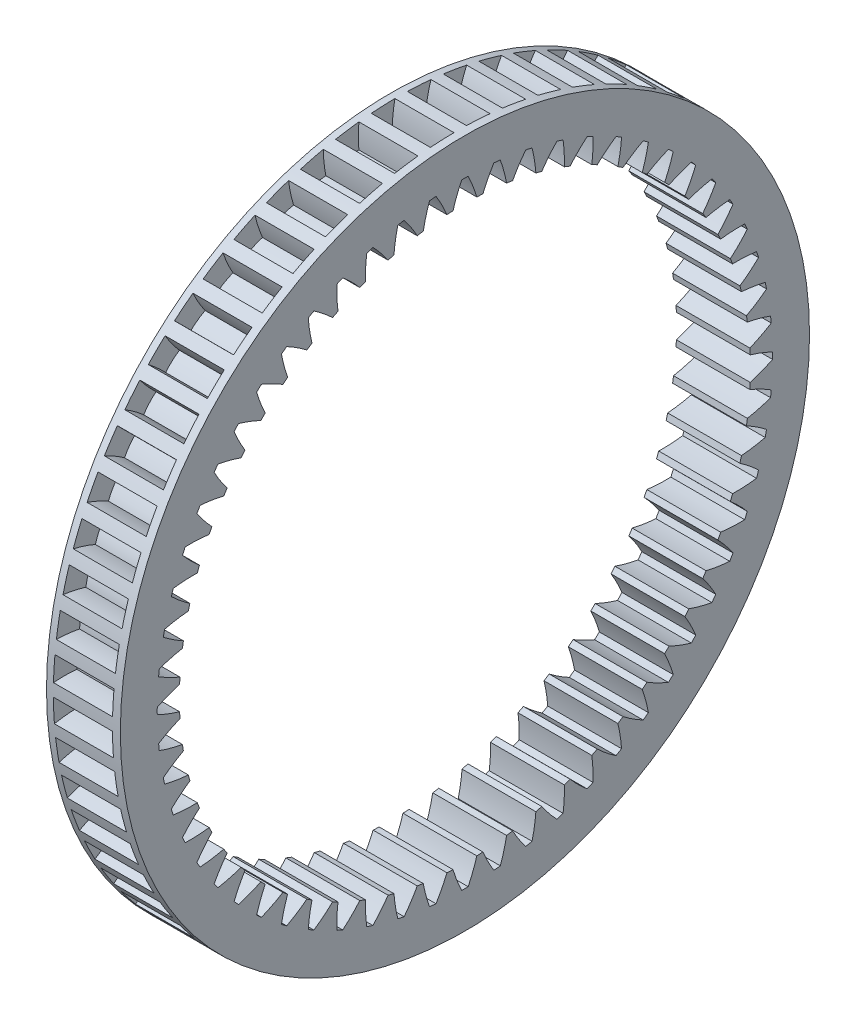
SolidWorks part; units mm, degrees
ref_plane "Front Plane" through (0, 0, 0) normal (0, 0, 1) x (1, 0, 0)
ref_plane "Top Plane" through (0, 0, 0) normal (0, 1, 0) x (1, 0, 0)
ref_plane "Right Plane" through (0, 0, 0) normal (1, 0, 0) x (0, 0, -1)
ref_plane "Plane1" through (0, 0, -17.7803) normal (0, 0, -1) x (-1, 0, 0)
sketch "Sketch1" plane through (0, 0, -17.7803) normal (0, 0, -1) x (-1, 0, 0)
  line L0 (3.4004, 104.6376) -> (3.4004, 34.6376)
  line L1 (3.4004, 34.6376) -> (5, 34.6376)
  line L2 (5, 34.6376) -> (5, 104.6376)
  line L3 (5, 104.6376) -> (3.4004, 104.6376)
  line L4 (3.4004, 34.6376) -> (5, 34.6376) construction
revolve "Revolve1" add sketch "Sketch1" angle 360 about L4
sketch "Sketch2" plane through (-5, 0, 0) normal (-1, 0, 0) x (0, 0, 1)
  arc A0 (-82.8676, 39.5668) -> (-82.8676, 35.7793) centre (-70.1186, 37.6731) ccw
  arc A1 (-87.571, 40.0464) -> (-82.8676, 39.5668) centre (-82.6586, 64.9218) ccw
  arc A2 (-87.571, 40.0464) -> (-87.3292, 42.5713) centre (-17.7803, 34.6376) cw
  arc A3 (-82.3917, 42.5765) -> (-87.3292, 42.5713) centre (-84.8336, 17.3751) ccw
  arc A4 (-81.9958, 46.3433) -> (-82.3917, 42.5765) centre (-69.5146, 43.1273) ccw
  arc A5 (-86.6233, 47.3118) -> (-81.9958, 46.3433) centre (-79.1376, 71.5375) ccw
  arc A6 (-86.6233, 47.3118) -> (-86.1189, 49.7977) centre (-17.7803, 34.6376) cw
  arc A7 (-81.2079, 49.2868) -> (-86.1189, 49.7977) centre (-86.2707, 24.4786) ccw
  arc A8 (-80.4204, 52.9915) -> (-81.2079, 49.2868) centre (-68.3437, 48.4885) ccw
  arc A9 (-84.9214, 54.4385) -> (-80.4204, 52.9915) centre (-74.9444, 77.749) ccw
  arc A10 (-84.9214, 54.4385) -> (-84.1599, 56.858) centre (-17.7803, 34.6376) cw
  arc A11 (-79.3291, 55.8365) -> (-84.1599, 56.858) centre (-86.9574, 31.6935) ccw
  arc A12 (-78.1587, 59.4386) -> (-79.3291, 55.8365) centre (-66.6189, 53.6979) ccw
  arc A13 (-82.4838, 61.3481) -> (-78.1587, 59.4386) centre (-70.1249, 83.4881) ccw
  arc A14 (-82.4838, 61.3481) -> (-81.4736, 63.6748) centre (-17.7803, 34.6376) cw
  arc A15 (-76.7761, 62.154) -> (-81.4736, 63.6748) centre (-86.8862, 38.9406) ccw
  arc A16 (-75.2356, 65.614) -> (-76.7761, 62.154) centre (-64.359, 58.6985) ccw
  arc A17 (-79.3373, 67.9652) -> (-75.2356, 65.614) centre (-64.7319, 88.692) ccw
  arc A18 (-79.3373, 67.9652) -> (-78.0895, 70.1735) centre (-17.7803, 34.6376) cw
  arc A19 (-73.5766, 68.17) -> (-78.0895, 70.1735) centre (-86.0579, 46.1405) ccw
  arc A20 (-71.6829, 71.45) -> (-73.5766, 68.17) centre (-61.5888, 63.4355) ccw
  arc A21 (-75.5164, 74.2171) -> (-71.6829, 71.45) centre (-58.8244, 93.3036) ccw
  arc A22 (-75.5164, 74.2171) -> (-74.0446, 76.2828) centre (-17.7803, 34.6376) cw
  arc A23 (-69.7659, 73.8186) -> (-74.0446, 76.2828) centre (-84.4814, 53.2145) ccw
  arc A24 (-67.5397, 76.8827) -> (-69.7659, 73.8186) centre (-58.3386, 67.857) ccw
  arc A25 (-71.063, 80.0353) -> (-67.5397, 76.8827) centre (-52.4673, 97.2725) ccw
  arc A26 (-71.063, 80.0353) -> (-69.3832, 81.9359) centre (-17.7803, 34.6376) cw
  arc A27 (-65.3856, 79.0379) -> (-69.3832, 81.9359) centre (-82.1742, 60.0849) ccw
  arc A28 (-62.8513, 81.8526) -> (-65.3856, 79.0379) centre (-54.6441, 71.9145) ccw
  arc A29 (-66.0257, 85.3562) -> (-62.8513, 81.8526) centre (-45.7302, 100.5552) ccw
  arc A30 (-66.0257, 85.3562) -> (-64.1565, 87.0708) centre (-17.7803, 34.6376) cw
  arc A31 (-60.4837, 83.7708) -> (-64.1565, 87.0708) centre (-79.1615, 66.6765) ccw
  arc A32 (-57.669, 86.3051) -> (-60.4837, 83.7708) centre (-50.5456, 75.5636) ccw
  arc A33 (-60.4599, 90.1214) -> (-57.669, 86.3051) centre (-38.6868, 103.1157) ccw
  arc A34 (-60.4599, 90.1214) -> (-58.4217, 91.6312) centre (-17.7803, 34.6376) cw
  arc A35 (-55.1139, 87.9654) -> (-58.4217, 91.6312) centre (-75.4763, 72.917) ccw
  arc A36 (-52.0498, 90.1916) -> (-55.1139, 87.9654) centre (-46.0882, 78.7643) ccw
  arc A37 (-54.4264, 94.2787) -> (-52.0498, 90.1916) centre (-31.4144, 104.9258) ccw
  arc A38 (-54.4264, 94.2787) -> (-52.2416, 95.5672) centre (-17.7803, 34.6376) cw
  arc A39 (-49.3351, 91.5757) -> (-52.2416, 95.5672) centre (-71.1589, 78.7382) ccw
  arc A40 (-46.0551, 93.4694) -> (-49.3351, 91.5757) centre (-41.3206, 81.4816) ccw
  arc A41 (-47.9915, 97.7825) -> (-46.0551, 93.4694) centre (-23.9925, 105.966) ccw
  arc A42 (-47.9915, 97.7825) -> (-45.684, 98.8356) centre (-17.7803, 34.6376) cw
  arc A43 (-43.2106, 94.5621) -> (-45.684, 98.8356) centre (-66.2567, 84.0762) ccw
  arc A44 (-39.7506, 96.1027) -> (-43.2106, 94.5621) centre (-36.2951, 83.6856) ccw
  arc A45 (-41.2256, 100.5945) -> (-39.7506, 96.1027) centre (-16.5027, 106.2246) ccw
  arc A46 (-41.2256, 100.5945) -> (-38.8206, 101.4006) centre (-17.7803, 34.6376) cw
  arc A47 (-36.8075, 96.8921) -> (-38.8206, 101.4006) centre (-60.8234, 88.8726) ccw
  arc A48 (-33.2054, 98.0625) -> (-36.8075, 96.8921) centre (-31.0668, 85.3523) ccw
  arc A49 (-34.2027, 102.6839) -> (-33.2054, 98.0625) centre (-9.0268, 105.6989) ccw
  arc A50 (-34.2027, 102.6839) -> (-31.7267, 103.2342) centre (-17.7803, 34.6376) cw
  arc A51 (-30.1959, 98.5399) -> (-31.7267, 103.2342) centre (-54.9185, 93.0747) ccw
  arc A52 (-26.4912, 99.3274) -> (-30.1959, 98.5399) centre (-25.6929, 86.4633) ccw
  arc A53 (-27, 104.0278) -> (-26.4912, 99.3274) centre (-1.6468, 104.3946) ccw
  arc A54 (-27, 104.0278) -> (-24.48, 104.3162) centre (-17.7803, 34.6376) cw
  arc A55 (-23.4483, 99.4876) -> (-24.48, 104.3162) centre (-48.6068, 96.6366) ccw
  arc A56 (-19.6815, 99.8835) -> (-23.4483, 99.4876) centre (-20.2323, 87.0064) ccw
  arc A57 (-19.6962, 104.6113) -> (-19.6815, 99.8835) centre (5.5564, 102.326) ccw
  arc A58 (-19.6962, 104.6113) -> (-17.1599, 104.6348) centre (-17.7803, 34.6376) cw
  arc A59 (-16.6385, 99.7248) -> (-17.1599, 104.6348) centre (-41.9572, 99.5192) ccw
  arc A60 (-12.8511, 99.7248) -> (-16.6385, 99.7248) centre (-14.7448, 86.9759) ccw
  arc A61 (-12.3715, 104.4283) -> (-12.8511, 99.7248) centre (12.5039, 99.5159) ccw
  arc A62 (-12.3715, 104.4283) -> (-9.8466, 104.1865) centre (-17.7803, 34.6376) cw
  arc A63 (-9.8413, 99.2489) -> (-9.8466, 104.1865) centre (-35.0428, 101.6909) ccw
  arc A64 (-6.0746, 98.853) -> (-9.8413, 99.2489) centre (-9.2906, 86.3718) ccw
  arc A65 (-5.106, 103.4806) -> (-6.0746, 98.853) centre (19.1197, 95.9949) ccw
  arc A66 (-5.106, 103.4806) -> (-2.6202, 102.9762) centre (-17.7803, 34.6376) cw
  arc A67 (-3.1311, 98.0652) -> (-2.6202, 102.9762) centre (-27.9393, 103.128) ccw
  arc A68 (0.5736, 97.2777) -> (-3.1311, 98.0652) centre (-3.9294, 85.201) ccw
  arc A69 (2.0206, 101.7787) -> (0.5736, 97.2777) centre (25.3311, 91.8017) ccw
  arc A70 (2.0206, 101.7787) -> (4.4401, 101.0172) centre (-17.7803, 34.6376) cw
  arc A71 (3.4187, 96.1864) -> (4.4401, 101.0172) centre (-20.7244, 103.8147) ccw
  arc A72 (7.0208, 95.016) -> (3.4187, 96.1864) centre (1.2801, 83.4762) ccw
  arc A73 (8.9303, 99.3411) -> (7.0208, 95.016) centre (31.0702, 86.9822) ccw
  arc A74 (8.9303, 99.3411) -> (11.2569, 98.3309) centre (-17.7803, 34.6376) cw
  arc A75 (9.7361, 93.6334) -> (11.2569, 98.3309) centre (-13.4773, 103.7435) ccw
  arc A76 (13.1962, 92.0929) -> (9.7361, 93.6334) centre (6.2807, 81.2163) ccw
  arc A77 (15.5473, 96.1946) -> (13.1962, 92.0929) centre (36.2741, 81.5892) ccw
  arc A78 (15.5473, 96.1946) -> (17.7556, 94.9468) centre (-17.7803, 34.6376) cw
  arc A79 (15.7521, 90.4339) -> (17.7556, 94.9468) centre (-6.2773, 102.9152) ccw
  arc A80 (19.0322, 88.5402) -> (15.7521, 90.4339) centre (11.0177, 78.4461) ccw
  arc A81 (21.7992, 92.3737) -> (19.0322, 88.5402) centre (40.8858, 75.6817) ccw
  arc A82 (21.7992, 92.3737) -> (23.865, 90.9019) centre (-17.7803, 34.6376) cw
  arc A83 (21.4007, 86.6232) -> (23.865, 90.9019) centre (0.7966, 101.3387) ccw
  arc A84 (24.4649, 84.397) -> (21.4007, 86.6232) centre (15.4391, 75.1959) ccw
  arc A85 (27.6175, 87.9203) -> (24.4649, 84.397) centre (44.8547, 69.3246) ccw
  arc A86 (27.6175, 87.9203) -> (29.5181, 86.2405) centre (-17.7803, 34.6376) cw
  arc A87 (26.6201, 82.2429) -> (29.5181, 86.2405) centre (7.667, 99.0315) ccw
  arc A88 (29.4347, 79.7085) -> (26.6201, 82.2429) centre (19.4967, 71.5014) ccw
  arc A89 (32.9383, 82.883) -> (29.4347, 79.7085) centre (48.1373, 62.5875) ccw
  arc A90 (32.9383, 82.883) -> (34.6529, 81.0138) centre (-17.7803, 34.6376) cw
  arc A91 (31.353, 77.341) -> (34.6529, 81.0138) centre (14.2586, 96.0188) ccw
  arc A92 (33.8873, 74.5263) -> (31.353, 77.341) centre (23.1458, 67.4029) ccw
  arc A93 (37.7035, 77.3172) -> (33.8873, 74.5263) centre (50.6978, 55.5441) ccw
  arc A94 (37.7035, 77.3172) -> (39.2133, 75.279) centre (-17.7803, 34.6376) cw
  arc A95 (35.5475, 71.9712) -> (39.2133, 75.279) centre (20.4992, 92.3336) ccw
  arc A96 (37.7738, 68.9071) -> (35.5475, 71.9712) centre (26.3465, 62.9455) ccw
  arc A97 (41.8608, 71.2837) -> (37.7738, 68.9071) centre (52.508, 48.2716) ccw
  arc A98 (41.8608, 71.2837) -> (43.1493, 69.0989) centre (-17.7803, 34.6376) cw
  arc A99 (39.1578, 66.1924) -> (43.1493, 69.0989) centre (26.3204, 88.0162) ccw
  arc A100 (41.0516, 62.9124) -> (39.1578, 66.1924) centre (29.0637, 58.1779) ccw
  arc A101 (45.3646, 64.8488) -> (41.0516, 62.9124) centre (53.5481, 40.8498) ccw
  arc A102 (45.3646, 64.8488) -> (46.4177, 62.5413) centre (-17.7803, 34.6376) cw
  arc A103 (42.1443, 60.0679) -> (46.4177, 62.5413) centre (31.6584, 83.114) ccw
  arc A104 (43.6848, 56.6079) -> (42.1443, 60.0679) centre (31.2678, 53.1524) ccw
  arc A105 (48.1767, 58.0829) -> (43.6848, 56.6079) centre (53.8067, 33.36) ccw
  arc A106 (48.1767, 58.0829) -> (48.9828, 55.6779) centre (-17.7803, 34.6376) cw
  arc A107 (44.4742, 53.6648) -> (48.9828, 55.6779) centre (36.4547, 77.6807) ccw
  arc A108 (45.6446, 50.0627) -> (44.4742, 53.6648) centre (32.9344, 47.9241) ccw
  arc A109 (50.266, 51.06) -> (45.6446, 50.0627) centre (53.281, 25.8841) ccw
  arc A110 (50.266, 51.06) -> (50.8163, 48.584) centre (-17.7803, 34.6376) cw
  arc A111 (46.1221, 47.0532) -> (50.8163, 48.584) centre (40.6568, 71.7758) ccw
  arc A112 (46.9095, 43.3485) -> (46.1221, 47.0532) centre (34.0454, 42.5502) ccw
  arc A113 (51.6099, 43.8573) -> (46.9095, 43.3485) centre (51.9767, 18.5041) ccw
  arc A114 (51.6099, 43.8573) -> (51.8984, 41.3373) centre (-17.7803, 34.6376) cw
  arc A115 (47.0698, 40.3056) -> (51.8984, 41.3373) centre (44.2187, 65.464) ccw
  arc A116 (47.4657, 36.5388) -> (47.0698, 40.3056) centre (34.5886, 37.0896) ccw
  arc A117 (52.1935, 36.5535) -> (47.4657, 36.5388) centre (49.9082, 11.3009) ccw
  arc A118 (52.1935, 36.5535) -> (52.217, 34.0172) centre (-17.7803, 34.6376) cw
  arc A119 (47.307, 33.4958) -> (52.217, 34.0172) centre (47.1013, 58.8145) ccw
  arc A120 (47.307, 29.7083) -> (47.307, 33.4958) centre (34.558, 31.6021) ccw
  arc A121 (52.0104, 29.2288) -> (47.307, 29.7083) centre (47.098, 4.3534) ccw
  arc A122 (52.0104, 29.2288) -> (51.7687, 26.7039) centre (-17.7803, 34.6376) cw
  arc A123 (46.8311, 26.6986) -> (51.7687, 26.7039) centre (49.2731, 51.9001) ccw
  arc A124 (46.4352, 22.9319) -> (46.8311, 26.6986) centre (33.954, 26.1479) ccw
  arc A125 (51.0627, 21.9633) -> (46.4352, 22.9319) centre (43.5771, -2.2624) ccw
  arc A126 (51.0627, 21.9633) -> (50.5584, 19.4775) centre (-17.7803, 34.6376) cw
  arc A127 (45.6473, 19.9884) -> (50.5584, 19.4775) centre (50.7102, 44.7965) ccw
  arc A128 (44.8598, 16.2837) -> (45.6473, 19.9884) centre (32.7832, 20.7867) ccw
  arc A129 (49.3608, 14.8367) -> (44.8598, 16.2837) centre (39.3838, -8.4738) ccw
  arc A130 (49.3608, 14.8367) -> (48.5993, 12.4172) centre (-17.7803, 34.6376) cw
  arc A131 (43.7686, 13.4386) -> (48.5993, 12.4172) centre (51.3969, 37.5817) ccw
  arc A132 (42.5982, 9.8365) -> (43.7686, 13.4386) centre (31.0584, 15.5772) ccw
  arc A133 (46.9232, 7.927) -> (42.5982, 9.8365) centre (34.5643, -14.2129) ccw
  arc A134 (46.9232, 7.927) -> (45.913, 5.6004) centre (-17.7803, 34.6376) cw
  arc A135 (41.2155, 7.1212) -> (45.913, 5.6004) centre (51.3257, 30.3346) ccw
  arc A136 (39.675, 3.6611) -> (41.2155, 7.1212) centre (28.7985, 10.5766) ccw
  arc A137 (43.7768, 1.31) -> (39.675, 3.6611) centre (29.1713, -19.4168) ccw
  arc A138 (43.7768, 1.31) -> (42.5289, -0.8983) centre (-17.7803, 34.6376) cw
  arc A139 (38.0161, 1.1052) -> (42.5289, -0.8983) centre (50.4973, 23.1346) ccw
  arc A140 (36.1223, -2.1749) -> (38.0161, 1.1052) centre (26.0283, 5.8396) ccw
  arc A141 (39.9559, -4.9419) -> (36.1223, -2.1749) centre (23.2639, -24.0285) ccw
  arc A142 (39.9559, -4.9419) -> (38.484, -7.0077) centre (-17.7803, 34.6376) cw
  arc A143 (34.2053, -4.5435) -> (38.484, -7.0077) centre (48.9209, 16.0607) ccw
  arc A144 (31.9791, -7.6076) -> (34.2053, -4.5435) centre (22.7781, 1.4181) ccw
  arc A145 (35.5024, -10.7602) -> (31.9791, -7.6076) centre (16.9068, -27.9974) ccw
  arc A146 (35.5024, -10.7602) -> (33.8227, -12.6608) centre (-17.7803, 34.6376) cw
  arc A147 (29.825, -9.7628) -> (33.8227, -12.6608) centre (46.6137, 9.1903) ccw
  arc A148 (27.2907, -12.5774) -> (29.825, -9.7628) centre (19.0835, -2.6394) ccw
  arc A149 (30.4652, -16.081) -> (27.2907, -12.5774) centre (10.1696, -31.28) ccw
  arc A150 (30.4652, -16.081) -> (28.596, -17.7956) centre (-17.7803, 34.6376) cw
  arc A151 (24.9231, -14.4957) -> (28.596, -17.7956) centre (43.6009, 2.5987) ccw
  arc A152 (22.1085, -17.03) -> (24.9231, -14.4957) centre (14.9851, -6.2885) ccw
  arc A153 (24.8993, -20.8462) -> (22.1085, -17.03) centre (3.1262, -33.8405) ccw
  arc A154 (24.8993, -20.8462) -> (22.8612, -22.3561) centre (-17.7803, 34.6376) cw
  arc A155 (19.5534, -18.6902) -> (22.8612, -22.3561) centre (39.9157, -3.6419) ccw
  arc A156 (16.4892, -20.9165) -> (19.5534, -18.6902) centre (10.5276, -9.4892) ccw
  arc A157 (18.8659, -25.0035) -> (16.4892, -20.9165) centre (-4.1462, -35.6507) ccw
  arc A158 (18.8659, -25.0035) -> (16.6811, -26.292) centre (-17.7803, 34.6376) cw
  arc A159 (13.7746, -22.3005) -> (16.6811, -26.292) centre (35.5984, -9.4631) ccw
  arc A160 (10.4945, -24.1943) -> (13.7746, -22.3005) centre (5.76, -12.2064) ccw
  arc A161 (12.4309, -28.5074) -> (10.4945, -24.1943) centre (-11.568, -36.6908) ccw
  arc A162 (12.4309, -28.5074) -> (10.1234, -29.5604) centre (-17.7803, 34.6376) cw
  arc A163 (7.6501, -25.287) -> (10.1234, -29.5604) centre (30.6962, -14.8011) ccw
  arc A164 (4.19, -26.8275) -> (7.6501, -25.287) centre (0.7346, -14.4105) ccw
  arc A165 (5.665, -31.3194) -> (4.19, -26.8275) centre (-19.0579, -36.9494) ccw
  arc A166 (5.665, -31.3194) -> (3.26, -32.1255) centre (-17.7803, 34.6376) cw
  arc A167 (1.2469, -27.6169) -> (3.26, -32.1255) centre (25.2629, -19.5974) ccw
  arc A168 (-2.3552, -28.7873) -> (1.2469, -27.6169) centre (-4.4938, -16.0771) ccw
  arc A169 (-1.3578, -33.4088) -> (-2.3552, -28.7873) centre (-26.5338, -36.4237) ccw
  arc A170 (-1.3578, -33.4088) -> (-3.8339, -33.9591) centre (-17.7803, 34.6376) cw
  arc A171 (-5.3647, -29.2648) -> (-3.8339, -33.9591) centre (19.358, -23.7995) ccw
  arc A172 (-9.0694, -30.0522) -> (-5.3647, -29.2648) centre (-9.8677, -17.1881) ccw
  arc A173 (-8.5606, -34.7526) -> (-9.0694, -30.0522) centre (-33.9138, -35.1194) ccw
  arc A174 (-8.5606, -34.7526) -> (-11.0806, -35.0411) centre (-17.7803, 34.6376) cw
  arc A175 (-12.1123, -30.2125) -> (-11.0806, -35.0411) centre (13.0462, -27.3614) ccw
  arc A176 (-15.879, -30.6084) -> (-12.1123, -30.2125) centre (-15.3283, -17.7313) ccw
  arc A177 (-15.8643, -35.3362) -> (-15.879, -30.6084) centre (-41.117, -33.0509) ccw
  arc A178 (-15.8643, -35.3362) -> (-18.4007, -35.3597) centre (-17.7803, 34.6376) cw
  arc A179 (-18.922, -30.4497) -> (-18.4007, -35.3597) centre (6.3967, -30.244) ccw
  arc A180 (-22.7095, -30.4497) -> (-18.922, -30.4497) centre (-20.8158, -17.7007) ccw
  arc A181 (-23.1891, -35.1531) -> (-22.7095, -30.4497) centre (-48.0645, -30.2407) ccw
  arc A182 (-23.1891, -35.1531) -> (-25.714, -34.9114) centre (-17.7803, 34.6376) cw
  arc A183 (-25.7192, -29.9738) -> (-25.714, -34.9114) centre (-0.5178, -32.4158) ccw
  arc A184 (-29.486, -29.5779) -> (-25.7192, -29.9738) centre (-26.27, -17.0967) ccw
  arc A185 (-30.4546, -34.2055) -> (-29.486, -29.5779) centre (-54.6802, -26.7198) ccw
  arc A186 (-30.4546, -34.2055) -> (-32.9404, -33.7011) centre (-17.7803, 34.6376) cw
  arc A187 (-32.4295, -28.79) -> (-32.9404, -33.7011) centre (-7.6213, -33.8529) ccw
  arc A188 (-36.1342, -28.0025) -> (-32.4295, -28.79) centre (-31.6312, -15.9259) ccw
  arc A189 (-37.5812, -32.5035) -> (-36.1342, -28.0025) centre (-60.8917, -22.5266) ccw
  arc A190 (-37.5812, -32.5035) -> (-40.0007, -31.7421) centre (-17.7803, 34.6376) cw
  arc A191 (-38.9792, -26.9113) -> (-40.0007, -31.7421) centre (-14.8362, -34.5396) ccw
  arc A192 (-42.5813, -25.7409) -> (-38.9792, -26.9113) centre (-36.8406, -14.2011) ccw
  arc A193 (-44.4909, -30.0659) -> (-42.5813, -25.7409) centre (-66.6308, -17.707) ccw
  arc A194 (-44.4909, -30.0659) -> (-46.8175, -29.0558) centre (-17.7803, 34.6376) cw
  arc A195 (-45.2967, -24.3582) -> (-46.8175, -29.0558) centre (-22.0833, -34.4684) ccw
  arc A196 (-48.7567, -22.8177) -> (-45.2967, -24.3582) centre (-41.8412, -11.9412) ccw
  arc A197 (-51.1079, -26.9195) -> (-48.7567, -22.8177) centre (-71.8347, -12.314) ccw
  arc A198 (-51.1079, -26.9195) -> (-53.3162, -25.6716) centre (-17.7803, 34.6376) cw
  arc A199 (-51.3127, -21.1588) -> (-53.3162, -25.6716) centre (-29.2832, -33.64) ccw
  arc A200 (-54.5928, -19.265) -> (-51.3127, -21.1588) centre (-46.5782, -9.171) ccw
  arc A201 (-57.3598, -23.0986) -> (-54.5928, -19.265) centre (-76.4463, -6.4066) ccw
  arc A202 (-57.3598, -23.0986) -> (-59.4255, -21.6267) centre (-17.7803, 34.6376) cw
  arc A203 (-56.9613, -17.348) -> (-59.4255, -21.6267) centre (-36.3572, -32.0636) ccw
  arc A204 (-60.0255, -15.1218) -> (-56.9613, -17.348) centre (-50.9997, -5.9208) ccw
  arc A205 (-63.178, -18.6451) -> (-60.0255, -15.1218) centre (-80.4152, -0.0495) ccw
  arc A206 (-63.178, -18.6451) -> (-65.0786, -16.9654) centre (-17.7803, 34.6376) cw
  arc A207 (-62.1806, -12.9677) -> (-65.0786, -16.9654) centre (-43.2276, -29.7564) ccw
  arc A208 (-64.9953, -10.4334) -> (-62.1806, -12.9677) centre (-55.0572, -2.2262) ccw
  arc A209 (-68.4989, -13.6079) -> (-64.9953, -10.4334) centre (-83.6979, 6.6877) ccw
  arc A210 (-68.4989, -13.6079) -> (-70.2135, -11.7387) centre (-17.7803, 34.6376) cw
  arc A211 (-66.9135, -8.0658) -> (-70.2135, -11.7387) centre (-49.8192, -26.7437) ccw
  arc A212 (-69.4479, -5.2512) -> (-66.9135, -8.0658) centre (-58.7063, 1.8722) ccw
  arc A213 (-73.2641, -8.042) -> (-69.4479, -5.2512) centre (-86.2584, 13.7311) ccw
  arc A214 (-73.2641, -8.042) -> (-74.7739, -6.0039) centre (-17.7803, 34.6376) cw
  arc A215 (-71.1081, -2.6961) -> (-74.7739, -6.0039) centre (-56.0598, -23.0584) ccw
  arc A216 (-73.3343, 0.3681) -> (-71.1081, -2.6961) centre (-61.9071, 6.3297) ccw
  arc A217 (-77.4214, -2.0086) -> (-73.3343, 0.3681) centre (-88.0686, 21.0035) ccw
  arc A218 (-77.4214, -2.0086) -> (-78.7099, 0.1762) centre (-17.7803, 34.6376) cw
  arc A219 (-74.7184, 3.0827) -> (-78.7099, 0.1762) centre (-61.8809, -18.7411) ccw
  arc A220 (-76.6121, 6.3628) -> (-74.7184, 3.0827) centre (-64.6243, 11.0972) ccw
  arc A221 (-80.9252, 4.4264) -> (-76.6121, 6.3628) centre (-89.1087, 28.4253) ccw
  arc A222 (-80.9252, 4.4264) -> (-81.9783, 6.7339) centre (-17.7803, 34.6376) cw
  arc A223 (-77.7049, 9.2072) -> (-81.9783, 6.7339) centre (-67.2189, -13.8389) ccw
  arc A224 (-79.2454, 12.6673) -> (-77.7049, 9.2072) centre (-66.8283, 16.1227) ccw
  arc A225 (-83.7372, 11.1923) -> (-79.2454, 12.6673) centre (-89.3673, 35.9152) ccw
  arc A226 (-83.7372, 11.1923) -> (-84.5433, 13.5973) centre (-17.7803, 34.6376) cw
  arc A227 (-80.0348, 15.6104) -> (-84.5433, 13.5973) centre (-72.0153, -8.4056) ccw
  arc A228 (-81.2052, 19.2125) -> (-80.0348, 15.6104) centre (-68.495, 21.3511) ccw
  arc A229 (-85.8266, 18.2151) -> (-81.2052, 19.2125) centre (-88.8416, 43.3911) ccw
  arc A230 (-85.8266, 18.2151) -> (-86.3769, 20.6912) centre (-17.7803, 34.6376) cw
  arc A231 (-81.6826, 22.222) -> (-86.3769, 20.6912) centre (-76.2174, -2.5007) ccw
  arc A232 (-82.4701, 25.9267) -> (-81.6826, 22.222) centre (-69.606, 26.725) ccw
  arc A233 (-87.1705, 25.4179) -> (-82.4701, 25.9267) centre (-87.5373, 50.771) ccw
  arc A234 (-87.1705, 25.4179) -> (-87.4589, 27.9379) centre (-17.7803, 34.6376) cw
  arc A235 (-82.6303, 28.9696) -> (-87.4589, 27.9379) centre (-79.7793, 3.8111) ccw
  arc A236 (-83.0262, 32.7363) -> (-82.6303, 28.9696) centre (-70.1491, 32.1856) ccw
  arc A237 (-87.7541, 32.7216) -> (-83.0262, 32.7363) centre (-85.4688, 57.9743) ccw
  arc A238 (-87.7541, 32.7216) -> (-87.7775, 35.258) centre (-17.7803, 34.6376) cw
  arc A239 (-82.8676, 35.7793) -> (-87.7775, 35.258) centre (-82.6619, 10.4606) ccw
extrude "Boss-Extrude1" add sketch "Sketch2" along normal blind 12
sketch "Sketch3" plane through (-17, 0, 0) normal (-1, 0, 0) x (0, 0, 1)
  circle A0 centre (-17.7803, 34.6376) radius 70
extrude "Boss-Extrude2" add sketch "Sketch3" along normal blind 1.4004
sketch "Sketch4" plane through (-18.4004, 0, 0) normal (-1, 0, 0) x (0, 0, 1)
  arc A0 (-23.6596, 96.8614) -> (-24.9665, 96.7241) centre (-17.7803, 34.6376) ccw
  arc A1 (-24.9665, 96.7241) -> (-26.2415, 92.0171) centre (3.2567, 86.5531) ccw
  arc A2 (-26.2415, 92.0171) -> (-27.4644, 91.8234) centre (-17.7803, 34.6376) ccw
  arc A3 (-27.4644, 91.8234) -> (-30.1315, 95.906) centre (-53.8304, 77.5114) ccw
  arc A4 (-30.1315, 95.906) -> (-31.417, 95.6328) centre (-17.7803, 34.6376) ccw
  arc A5 (-31.417, 95.6328) -> (-32.1929, 90.8183) centre (-2.2852, 88.4677) ccw
  arc A6 (-32.1929, 90.8183) -> (-33.3889, 90.4979) centre (-17.7803, 34.6376) ccw
  arc A7 (-33.3889, 90.4979) -> (-36.4682, 94.2793) centre (-58.1145, 73.5083) ccw
  arc A8 (-36.4682, 94.2793) -> (-37.718, 93.8732) centre (-17.7803, 34.6376) ccw
  arc A9 (-37.718, 93.8732) -> (-37.9865, 89.004) centre (-7.9968, 89.7925) ccw
  arc A10 (-37.9865, 89.004) -> (-39.1424, 88.5603) centre (-17.7803, 34.6376) ccw
  arc A11 (-39.1424, 88.5603) -> (-42.6001, 91.9992) centre (-61.9566, 69.0793) ccw
  arc A12 (-42.6001, 91.9992) -> (-43.8006, 91.4647) centre (-17.7803, 34.6376) ccw
  arc A13 (-43.8006, 91.4647) -> (-43.5586, 86.5941) centre (-13.8157, 90.513) ccw
  arc A14 (-43.5586, 86.5941) -> (-44.6618, 86.032) centre (-17.7803, 34.6376) ccw
  arc A15 (-44.6618, 86.032) -> (-48.46, 89.0906) centre (-65.3148, 64.2729) ccw
  arc A16 (-48.46, 89.0906) -> (-49.5981, 88.4335) centre (-17.7803, 34.6376) ccw
  arc A17 (-49.5981, 88.4335) -> (-48.8483, 83.6149) centre (-19.678, 90.6213) ccw
  arc A18 (-48.8483, 83.6149) -> (-49.8868, 82.9405) centre (-17.7803, 34.6376) ccw
  arc A19 (-49.8868, 82.9405) -> (-53.9838, 85.5854) centre (-68.1521, 59.1418) ccw
  arc A20 (-53.9838, 85.5854) -> (-55.047, 84.8129) centre (-17.7803, 34.6376) ccw
  arc A21 (-55.047, 84.8129) -> (-53.7977, 80.0991) centre (-25.5195, 90.1163) ccw
  arc A22 (-53.7977, 80.0991) -> (-54.7599, 79.3199) centre (-17.7803, 34.6376) ccw
  arc A23 (-54.7599, 79.3199) -> (-59.111, 81.522) centre (-70.4375, 53.7423) ccw
  arc A24 (-59.111, 81.522) -> (-60.0876, 80.6426) centre (-17.7803, 34.6376) ccw
  arc A25 (-60.0876, 80.6426) -> (-58.3524, 76.0852) centre (-31.2762, 89.0034) ccw
  arc A26 (-58.3524, 76.0852) -> (-59.2279, 75.2097) centre (-17.7803, 34.6376) ccw
  arc A27 (-59.2279, 75.2097) -> (-63.7853, 76.9449) centre (-72.1461, 48.1335) ccw
  arc A28 (-63.7853, 76.9449) -> (-64.6647, 75.9683) centre (-17.7803, 34.6376) ccw
  arc A29 (-64.6647, 75.9683) -> (-62.4626, 71.6172) centre (-36.885, 87.2948) ccw
  arc A30 (-62.4626, 71.6172) -> (-63.2418, 70.655) centre (-17.7803, 34.6376) ccw
  arc A31 (-63.2418, 70.655) -> (-67.9556, 71.9043) centre (-73.259, 42.3768) ccw
  arc A32 (-67.9556, 71.9043) -> (-68.7281, 70.8411) centre (-17.7803, 34.6376) ccw
  arc A33 (-68.7281, 70.8411) -> (-66.0832, 66.744) centre (-42.2846, 85.0094) ccw
  arc A34 (-66.0832, 66.744) -> (-66.7576, 65.7056) centre (-17.7803, 34.6376) ccw
  arc A35 (-66.7576, 65.7056) -> (-71.5762, 66.4554) centre (-73.764, 36.5353) ccw
  arc A36 (-71.5762, 66.4554) -> (-72.2333, 65.3173) centre (-17.7803, 34.6376) ccw
  arc A37 (-72.2333, 65.3173) -> (-69.1747, 61.5191) centre (-47.4156, 82.1721) ccw
  arc A38 (-69.1747, 61.5191) -> (-69.7368, 60.4159) centre (-17.7803, 34.6376) ccw
  arc A39 (-69.7368, 60.4159) -> (-74.6074, 60.6579) centre (-73.6557, 30.673) ccw
  arc A40 (-74.6074, 60.6579) -> (-75.1419, 59.4573) centre (-17.7803, 34.6376) ccw
  arc A41 (-75.1419, 59.4573) -> (-71.703, 55.9997) centre (-52.222, 78.8139) ccw
  arc A42 (-71.703, 55.9997) -> (-72.1467, 54.8438) centre (-17.7803, 34.6376) ccw
  arc A43 (-72.1467, 54.8438) -> (-77.0159, 54.5753) centre (-72.9352, 24.8541) ccw
  arc A44 (-77.0159, 54.5753) -> (-77.422, 53.3255) centre (-17.7803, 34.6376) ccw
  arc A45 (-77.422, 53.3255) -> (-73.6406, 50.2462) centre (-56.651, 74.9718) ccw
  arc A46 (-73.6406, 50.2462) -> (-73.961, 49.0502) centre (-17.7803, 34.6376) ccw
  arc A47 (-73.961, 49.0502) -> (-78.7755, 48.2743) centre (-71.6104, 19.1425) ccw
  arc A48 (-78.7755, 48.2743) -> (-79.0487, 46.9888) centre (-17.7803, 34.6376) ccw
  arc A49 (-79.0487, 46.9888) -> (-74.9661, 44.3217) centre (-60.6541, 70.6877) ccw
  arc A50 (-74.9661, 44.3217) -> (-75.1598, 43.0988) centre (-17.7803, 34.6376) ccw
  arc A51 (-75.1598, 43.0988) -> (-79.8668, 41.8238) centre (-69.6958, 13.6006) ccw
  arc A52 (-79.8668, 41.8238) -> (-80.0041, 40.5169) centre (-17.7803, 34.6376) ccw
  arc A53 (-80.0041, 40.5169) -> (-75.6651, 38.2911) centre (-64.1875, 66.0087) ccw
  arc A54 (-75.6651, 38.2911) -> (-75.7299, 37.0547) centre (-17.7803, 34.6376) ccw
  arc A55 (-75.7299, 37.0547) -> (-80.2778, 35.2947) centre (-67.2125, 8.2892) ccw
  arc A56 (-80.2778, 35.2947) -> (-80.2778, 33.9805) centre (-17.7803, 34.6376) ccw
  arc A57 (-80.2778, 33.9805) -> (-75.7299, 32.2205) centre (-67.2125, 60.986) ccw
  arc A58 (-75.7299, 32.2205) -> (-75.6651, 30.984) centre (-17.7803, 34.6376) ccw
  arc A59 (-75.6651, 30.984) -> (-80.0041, 28.7583) centre (-64.1875, 3.2664) ccw
  arc A60 (-80.0041, 28.7583) -> (-79.8668, 27.4513) centre (-17.7803, 34.6376) ccw
  arc A61 (-79.8668, 27.4513) -> (-75.1598, 26.1763) centre (-69.6958, 55.6746) ccw
  arc A62 (-75.1598, 26.1763) -> (-74.9661, 24.9534) centre (-17.7803, 34.6376) ccw
  arc A63 (-74.9661, 24.9534) -> (-79.0487, 22.2863) centre (-60.6541, -1.4126) ccw
  arc A64 (-79.0487, 22.2863) -> (-78.7755, 21.0009) centre (-17.7803, 34.6376) ccw
  arc A65 (-78.7755, 21.0009) -> (-73.961, 20.2249) centre (-71.6104, 50.1327) ccw
  arc A66 (-73.961, 20.2249) -> (-73.6406, 19.0289) centre (-17.7803, 34.6376) ccw
  arc A67 (-73.6406, 19.0289) -> (-77.422, 15.9497) centre (-56.651, -5.6966) ccw
  arc A68 (-77.422, 15.9497) -> (-77.0159, 14.6999) centre (-17.7803, 34.6376) ccw
  arc A69 (-77.0159, 14.6999) -> (-72.1467, 14.4314) centre (-72.9352, 44.421) ccw
  arc A70 (-72.1467, 14.4314) -> (-71.703, 13.2755) centre (-17.7803, 34.6376) ccw
  arc A71 (-71.703, 13.2755) -> (-75.1419, 9.8178) centre (-52.222, -9.5388) ccw
  arc A72 (-75.1419, 9.8178) -> (-74.6074, 8.6173) centre (-17.7803, 34.6376) ccw
  arc A73 (-74.6074, 8.6173) -> (-69.7368, 8.8592) centre (-73.6557, 38.6022) ccw
  arc A74 (-69.7368, 8.8592) -> (-69.1747, 7.756) centre (-17.7803, 34.6376) ccw
  arc A75 (-69.1747, 7.756) -> (-72.2333, 3.9578) centre (-47.4156, -12.8969) ccw
  arc A76 (-72.2333, 3.9578) -> (-71.5762, 2.8198) centre (-17.7803, 34.6376) ccw
  arc A77 (-71.5762, 2.8198) -> (-66.7576, 3.5695) centre (-73.764, 32.7399) ccw
  arc A78 (-66.7576, 3.5695) -> (-66.0832, 2.5311) centre (-17.7803, 34.6376) ccw
  arc A79 (-66.0832, 2.5311) -> (-68.7281, -1.566) centre (-42.2846, -15.7342) ccw
  arc A80 (-68.7281, -1.566) -> (-67.9556, -2.6291) centre (-17.7803, 34.6376) ccw
  arc A81 (-67.9556, -2.6291) -> (-63.2418, -1.3798) centre (-73.259, 26.8984) ccw
  arc A82 (-63.2418, -1.3798) -> (-62.4626, -2.342) centre (-17.7803, 34.6376) ccw
  arc A83 (-62.4626, -2.342) -> (-64.6647, -6.6931) centre (-36.885, -18.0197) ccw
  arc A84 (-64.6647, -6.6931) -> (-63.7853, -7.6698) centre (-17.7803, 34.6376) ccw
  arc A85 (-63.7853, -7.6698) -> (-59.2279, -5.9345) centre (-72.1461, 21.1417) ccw
  arc A86 (-59.2279, -5.9345) -> (-58.3524, -6.81) centre (-17.7803, 34.6376) ccw
  arc A87 (-58.3524, -6.81) -> (-60.0876, -11.3675) centre (-31.2762, -19.7282) ccw
  arc A88 (-60.0876, -11.3675) -> (-59.111, -12.2468) centre (-17.7803, 34.6376) ccw
  arc A89 (-59.111, -12.2468) -> (-54.7599, -10.0447) centre (-70.4375, 15.5328) ccw
  arc A90 (-54.7599, -10.0447) -> (-53.7977, -10.8239) centre (-17.7803, 34.6376) ccw
  arc A91 (-53.7977, -10.8239) -> (-55.047, -15.5378) centre (-25.5195, -20.8411) ccw
  arc A92 (-55.047, -15.5378) -> (-53.9838, -16.3102) centre (-17.7803, 34.6376) ccw
  arc A93 (-53.9838, -16.3102) -> (-49.8868, -13.6654) centre (-68.1521, 10.1333) ccw
  arc A94 (-49.8868, -13.6654) -> (-48.8483, -14.3397) centre (-17.7803, 34.6376) ccw
  arc A95 (-48.8483, -14.3397) -> (-49.5981, -19.1583) centre (-19.678, -21.3461) ccw
  arc A96 (-49.5981, -19.1583) -> (-48.46, -19.8154) centre (-17.7803, 34.6376) ccw
  arc A97 (-48.46, -19.8154) -> (-44.6618, -16.7568) centre (-65.3148, 5.0023) ccw
  arc A98 (-44.6618, -16.7568) -> (-43.5586, -17.3189) centre (-17.7803, 34.6376) ccw
  arc A99 (-43.5586, -17.3189) -> (-43.8006, -22.1895) centre (-13.8157, -21.2378) ccw
  arc A100 (-43.8006, -22.1895) -> (-42.6001, -22.724) centre (-17.7803, 34.6376) ccw
  arc A101 (-42.6001, -22.724) -> (-39.1424, -19.2851) centre (-61.9566, 0.1959) ccw
  arc A102 (-39.1424, -19.2851) -> (-37.9865, -19.7289) centre (-17.7803, 34.6376) ccw
  arc A103 (-37.9865, -19.7289) -> (-37.718, -24.5981) centre (-7.9968, -20.5173) ccw
  arc A104 (-37.718, -24.5981) -> (-36.4682, -25.0042) centre (-17.7803, 34.6376) ccw
  arc A105 (-36.4682, -25.0042) -> (-33.3889, -21.2227) centre (-58.1145, -4.2331) ccw
  arc A106 (-33.3889, -21.2227) -> (-32.1929, -21.5432) centre (-17.7803, 34.6376) ccw
  arc A107 (-32.1929, -21.5432) -> (-31.417, -26.3576) centre (-2.2852, -19.1925) ccw
  arc A108 (-31.417, -26.3576) -> (-30.1315, -26.6309) centre (-17.7803, 34.6376) ccw
  arc A109 (-30.1315, -26.6309) -> (-27.4644, -22.5482) centre (-53.8304, -8.2363) ccw
  arc A110 (-27.4644, -22.5482) -> (-26.2415, -22.7419) centre (-17.7803, 34.6376) ccw
  arc A111 (-26.2415, -22.7419) -> (-24.9665, -27.4489) centre (3.2567, -17.278) ccw
  arc A112 (-24.9665, -27.4489) -> (-23.6596, -27.5863) centre (-17.7803, 34.6376) ccw
  arc A113 (-23.6596, -27.5863) -> (-21.4338, -23.2472) centre (-49.1514, -11.7697) ccw
  arc A114 (-21.4338, -23.2472) -> (-20.1974, -23.312) centre (-17.7803, 34.6376) ccw
  arc A115 (-20.1974, -23.312) -> (-18.4374, -27.86) centre (8.5681, -14.7946) ccw
  arc A116 (-18.4374, -27.86) -> (-17.1232, -27.86) centre (-17.7803, 34.6376) ccw
  arc A117 (-17.1232, -27.86) -> (-15.3632, -23.312) centre (-44.1287, -14.7946) ccw
  arc A118 (-15.3632, -23.312) -> (-14.1267, -23.2472) centre (-17.7803, 34.6376) ccw
  arc A119 (-14.1267, -23.2472) -> (-11.901, -27.5863) centre (13.5909, -11.7697) ccw
  arc A120 (-11.901, -27.5863) -> (-10.594, -27.4489) centre (-17.7803, 34.6376) ccw
  arc A121 (-10.594, -27.4489) -> (-9.3191, -22.7419) centre (-38.8173, -17.278) ccw
  arc A122 (-9.3191, -22.7419) -> (-8.0961, -22.5482) centre (-17.7803, 34.6376) ccw
  arc A123 (-8.0961, -22.5482) -> (-5.429, -26.6309) centre (18.2699, -8.2363) ccw
  arc A124 (-5.429, -26.6309) -> (-4.1436, -26.3576) centre (-17.7803, 34.6376) ccw
  arc A125 (-4.1436, -26.3576) -> (-3.3676, -21.5432) centre (-33.2754, -19.1925) ccw
  arc A126 (-3.3676, -21.5432) -> (-2.1717, -21.2227) centre (-17.7803, 34.6376) ccw
  arc A127 (-2.1717, -21.2227) -> (0.9076, -25.0042) centre (22.5539, -4.2331) ccw
  arc A128 (0.9076, -25.0042) -> (2.1574, -24.5981) centre (-17.7803, 34.6376) ccw
  arc A129 (2.1574, -24.5981) -> (2.4259, -19.7289) centre (-27.5637, -20.5173) ccw
  arc A130 (2.4259, -19.7289) -> (3.5818, -19.2851) centre (-17.7803, 34.6376) ccw
  arc A131 (3.5818, -19.2851) -> (7.0395, -22.724) centre (26.3961, 0.1959) ccw
  arc A132 (7.0395, -22.724) -> (8.24, -22.1895) centre (-17.7803, 34.6376) ccw
  arc A133 (8.24, -22.1895) -> (7.9981, -17.3189) centre (-21.7449, -21.2378) ccw
  arc A134 (7.9981, -17.3189) -> (9.1013, -16.7568) centre (-17.7803, 34.6376) ccw
  arc A135 (9.1013, -16.7568) -> (12.8994, -19.8154) centre (29.7542, 5.0023) ccw
  arc A136 (12.8994, -19.8154) -> (14.0375, -19.1583) centre (-17.7803, 34.6376) ccw
  arc A137 (14.0375, -19.1583) -> (13.2878, -14.3397) centre (-15.8826, -21.3461) ccw
  arc A138 (13.2878, -14.3397) -> (14.3262, -13.6654) centre (-17.7803, 34.6376) ccw
  arc A139 (14.3262, -13.6654) -> (18.4233, -16.3102) centre (32.5915, 10.1333) ccw
  arc A140 (18.4233, -16.3102) -> (19.4864, -15.5378) centre (-17.7803, 34.6376) ccw
  arc A141 (19.4864, -15.5378) -> (18.2371, -10.8239) centre (-10.0411, -20.8411) ccw
  arc A142 (18.2371, -10.8239) -> (19.1993, -10.0447) centre (-17.7803, 34.6376) ccw
  arc A143 (19.1993, -10.0447) -> (23.5504, -12.2468) centre (34.877, 15.5328) ccw
  arc A144 (23.5504, -12.2468) -> (24.527, -11.3675) centre (-17.7803, 34.6376) ccw
  arc A145 (24.527, -11.3675) -> (22.7918, -6.81) centre (-4.2844, -19.7282) ccw
  arc A146 (22.7918, -6.81) -> (23.6673, -5.9345) centre (-17.7803, 34.6376) ccw
  arc A147 (23.6673, -5.9345) -> (28.2248, -7.6698) centre (36.5855, 21.1417) ccw
  arc A148 (28.2248, -7.6698) -> (29.1041, -6.6931) centre (-17.7803, 34.6376) ccw
  arc A149 (29.1041, -6.6931) -> (26.902, -2.342) centre (1.3245, -18.0197) ccw
  arc A150 (26.902, -2.342) -> (27.6812, -1.3798) centre (-17.7803, 34.6376) ccw
  arc A151 (27.6812, -1.3798) -> (32.3951, -2.6291) centre (37.6984, 26.8984) ccw
  arc A152 (32.3951, -2.6291) -> (33.1675, -1.566) centre (-17.7803, 34.6376) ccw
  arc A153 (33.1675, -1.566) -> (30.5227, 2.5311) centre (6.724, -15.7342) ccw
  arc A154 (30.5227, 2.5311) -> (31.197, 3.5695) centre (-17.7803, 34.6376) ccw
  arc A155 (31.197, 3.5695) -> (36.0156, 2.8198) centre (38.2034, 32.7399) ccw
  arc A156 (36.0156, 2.8198) -> (36.6727, 3.9578) centre (-17.7803, 34.6376) ccw
  arc A157 (36.6727, 3.9578) -> (33.6141, 7.756) centre (11.855, -12.8969) ccw
  arc A158 (33.6141, 7.756) -> (34.1762, 8.8592) centre (-17.7803, 34.6376) ccw
  arc A159 (34.1762, 8.8592) -> (39.0468, 8.6173) centre (38.0951, 38.6022) ccw
  arc A160 (39.0468, 8.6173) -> (39.5813, 9.8178) centre (-17.7803, 34.6376) ccw
  arc A161 (39.5813, 9.8178) -> (36.1424, 13.2755) centre (16.6614, -9.5388) ccw
  arc A162 (36.1424, 13.2755) -> (36.5862, 14.4314) centre (-17.7803, 34.6376) ccw
  arc A163 (36.5862, 14.4314) -> (41.4554, 14.6999) centre (37.3746, 44.421) ccw
  arc A164 (41.4554, 14.6999) -> (41.8615, 15.9497) centre (-17.7803, 34.6376) ccw
  arc A165 (41.8615, 15.9497) -> (38.08, 19.0289) centre (21.0904, -5.6966) ccw
  arc A166 (38.08, 19.0289) -> (38.4005, 20.2249) centre (-17.7803, 34.6376) ccw
  arc A167 (38.4005, 20.2249) -> (43.2149, 21.0009) centre (36.0498, 50.1327) ccw
  arc A168 (43.2149, 21.0009) -> (43.4882, 22.2863) centre (-17.7803, 34.6376) ccw
  arc A169 (43.4882, 22.2863) -> (39.4055, 24.9534) centre (25.0935, -1.4126) ccw
  arc A170 (39.4055, 24.9534) -> (39.5992, 26.1763) centre (-17.7803, 34.6376) ccw
  arc A171 (39.5992, 26.1763) -> (44.3062, 27.4513) centre (34.1353, 55.6746) ccw
  arc A172 (44.3062, 27.4513) -> (44.4436, 28.7583) centre (-17.7803, 34.6376) ccw
  arc A173 (44.4436, 28.7583) -> (40.1045, 30.984) centre (28.6269, 3.2664) ccw
  arc A174 (40.1045, 30.984) -> (40.1693, 32.2205) centre (-17.7803, 34.6376) ccw
  arc A175 (40.1693, 32.2205) -> (44.7173, 33.9805) centre (31.6519, 60.986) ccw
  arc A176 (44.7173, 33.9805) -> (44.7173, 35.2947) centre (-17.7803, 34.6376) ccw
  arc A177 (44.7173, 35.2947) -> (40.1693, 37.0547) centre (31.6519, 8.2892) ccw
  arc A178 (40.1693, 37.0547) -> (40.1045, 38.2911) centre (-17.7803, 34.6376) ccw
  arc A179 (40.1045, 38.2911) -> (44.4436, 40.5169) centre (28.6269, 66.0087) ccw
  arc A180 (44.4436, 40.5169) -> (44.3062, 41.8238) centre (-17.7803, 34.6376) ccw
  arc A181 (44.3062, 41.8238) -> (39.5992, 43.0988) centre (34.1353, 13.6006) ccw
  arc A182 (39.5992, 43.0988) -> (39.4055, 44.3217) centre (-17.7803, 34.6376) ccw
  arc A183 (39.4055, 44.3217) -> (43.4882, 46.9888) centre (25.0935, 70.6877) ccw
  arc A184 (43.4882, 46.9888) -> (43.2149, 48.2743) centre (-17.7803, 34.6376) ccw
  arc A185 (43.2149, 48.2743) -> (38.4005, 49.0502) centre (36.0498, 19.1425) ccw
  arc A186 (38.4005, 49.0502) -> (38.08, 50.2462) centre (-17.7803, 34.6376) ccw
  arc A187 (38.08, 50.2462) -> (41.8615, 53.3255) centre (21.0904, 74.9718) ccw
  arc A188 (41.8615, 53.3255) -> (41.4554, 54.5753) centre (-17.7803, 34.6376) ccw
  arc A189 (41.4554, 54.5753) -> (36.5862, 54.8438) centre (37.3746, 24.8541) ccw
  arc A190 (36.5862, 54.8438) -> (36.1424, 55.9997) centre (-17.7803, 34.6376) ccw
  arc A191 (36.1424, 55.9997) -> (39.5813, 59.4573) centre (16.6614, 78.8139) ccw
  arc A192 (39.5813, 59.4573) -> (39.0468, 60.6579) centre (-17.7803, 34.6376) ccw
  arc A193 (39.0468, 60.6579) -> (34.1762, 60.4159) centre (38.0951, 30.673) ccw
  arc A194 (34.1762, 60.4159) -> (33.6141, 61.5191) centre (-17.7803, 34.6376) ccw
  arc A195 (33.6141, 61.5191) -> (36.6727, 65.3173) centre (11.855, 82.1721) ccw
  arc A196 (36.6727, 65.3173) -> (36.0156, 66.4554) centre (-17.7803, 34.6376) ccw
  arc A197 (36.0156, 66.4554) -> (31.197, 65.7056) centre (38.2034, 36.5353) ccw
  arc A198 (31.197, 65.7056) -> (30.5227, 66.744) centre (-17.7803, 34.6376) ccw
  arc A199 (30.5227, 66.744) -> (33.1675, 70.8411) centre (6.724, 85.0094) ccw
  arc A200 (33.1675, 70.8411) -> (32.3951, 71.9043) centre (-17.7803, 34.6376) ccw
  arc A201 (32.3951, 71.9043) -> (27.6812, 70.655) centre (37.6984, 42.3768) ccw
  arc A202 (27.6812, 70.655) -> (26.902, 71.6172) centre (-17.7803, 34.6376) ccw
  arc A203 (26.902, 71.6172) -> (29.1041, 75.9683) centre (1.3245, 87.2948) ccw
  arc A204 (29.1041, 75.9683) -> (28.2248, 76.9449) centre (-17.7803, 34.6376) ccw
  arc A205 (28.2248, 76.9449) -> (23.6673, 75.2097) centre (36.5855, 48.1335) ccw
  arc A206 (23.6673, 75.2097) -> (22.7918, 76.0852) centre (-17.7803, 34.6376) ccw
  arc A207 (22.7918, 76.0852) -> (24.527, 80.6426) centre (-4.2844, 89.0034) ccw
  arc A208 (24.527, 80.6426) -> (23.5504, 81.522) centre (-17.7803, 34.6376) ccw
  arc A209 (23.5504, 81.522) -> (19.1993, 79.3199) centre (34.877, 53.7423) ccw
  arc A210 (19.1993, 79.3199) -> (18.2371, 80.0991) centre (-17.7803, 34.6376) ccw
  arc A211 (18.2371, 80.0991) -> (19.4864, 84.8129) centre (-10.0411, 90.1163) ccw
  arc A212 (19.4864, 84.8129) -> (18.4233, 85.5854) centre (-17.7803, 34.6376) ccw
  arc A213 (18.4233, 85.5854) -> (14.3262, 82.9405) centre (32.5915, 59.1418) ccw
  arc A214 (14.3262, 82.9405) -> (13.2878, 83.6149) centre (-17.7803, 34.6376) ccw
  arc A215 (13.2878, 83.6149) -> (14.0375, 88.4335) centre (-15.8826, 90.6213) ccw
  arc A216 (14.0375, 88.4335) -> (12.8994, 89.0906) centre (-17.7803, 34.6376) ccw
  arc A217 (12.8994, 89.0906) -> (9.1013, 86.032) centre (29.7542, 64.2729) ccw
  arc A218 (9.1013, 86.032) -> (7.9981, 86.5941) centre (-17.7803, 34.6376) ccw
  arc A219 (7.9981, 86.5941) -> (8.24, 91.4647) centre (-21.7449, 90.513) ccw
  arc A220 (8.24, 91.4647) -> (7.0395, 91.9992) centre (-17.7803, 34.6376) ccw
  arc A221 (7.0395, 91.9992) -> (3.5818, 88.5603) centre (26.3961, 69.0793) ccw
  arc A222 (3.5818, 88.5603) -> (2.4259, 89.004) centre (-17.7803, 34.6376) ccw
  arc A223 (2.4259, 89.004) -> (2.1574, 93.8732) centre (-27.5637, 89.7925) ccw
  arc A224 (2.1574, 93.8732) -> (0.9076, 94.2793) centre (-17.7803, 34.6376) ccw
  arc A225 (0.9076, 94.2793) -> (-2.1717, 90.4979) centre (22.5539, 73.5083) ccw
  arc A226 (-2.1717, 90.4979) -> (-3.3676, 90.8183) centre (-17.7803, 34.6376) ccw
  arc A227 (-3.3676, 90.8183) -> (-4.1436, 95.6328) centre (-33.2754, 88.4677) ccw
  arc A228 (-4.1436, 95.6328) -> (-5.429, 95.906) centre (-17.7803, 34.6376) ccw
  arc A229 (-5.429, 95.906) -> (-8.0961, 91.8234) centre (18.2699, 77.5114) ccw
  arc A230 (-8.0961, 91.8234) -> (-9.3191, 92.0171) centre (-17.7803, 34.6376) ccw
  arc A231 (-9.3191, 92.0171) -> (-10.594, 96.7241) centre (-38.8173, 86.5531) ccw
  arc A232 (-10.594, 96.7241) -> (-11.901, 96.8614) centre (-17.7803, 34.6376) ccw
  arc A233 (-11.901, 96.8614) -> (-14.1267, 92.5224) centre (13.5909, 81.0448) ccw
  arc A234 (-14.1267, 92.5224) -> (-15.3632, 92.5872) centre (-17.7803, 34.6376) ccw
  arc A235 (-15.3632, 92.5872) -> (-17.1232, 97.1351) centre (-44.1287, 84.0698) ccw
  arc A236 (-17.1232, 97.1351) -> (-18.4374, 97.1351) centre (-17.7803, 34.6376) ccw
  arc A237 (-18.4374, 97.1351) -> (-20.1974, 92.5872) centre (8.5681, 84.0698) ccw
  arc A238 (-20.1974, 92.5872) -> (-21.4338, 92.5224) centre (-17.7803, 34.6376) ccw
  arc A239 (-21.4338, 92.5224) -> (-23.6596, 96.8614) centre (-49.1514, 81.0448) ccw
extrude "Cut-Extrude1" cut sketch "Sketch4" against normal through all
